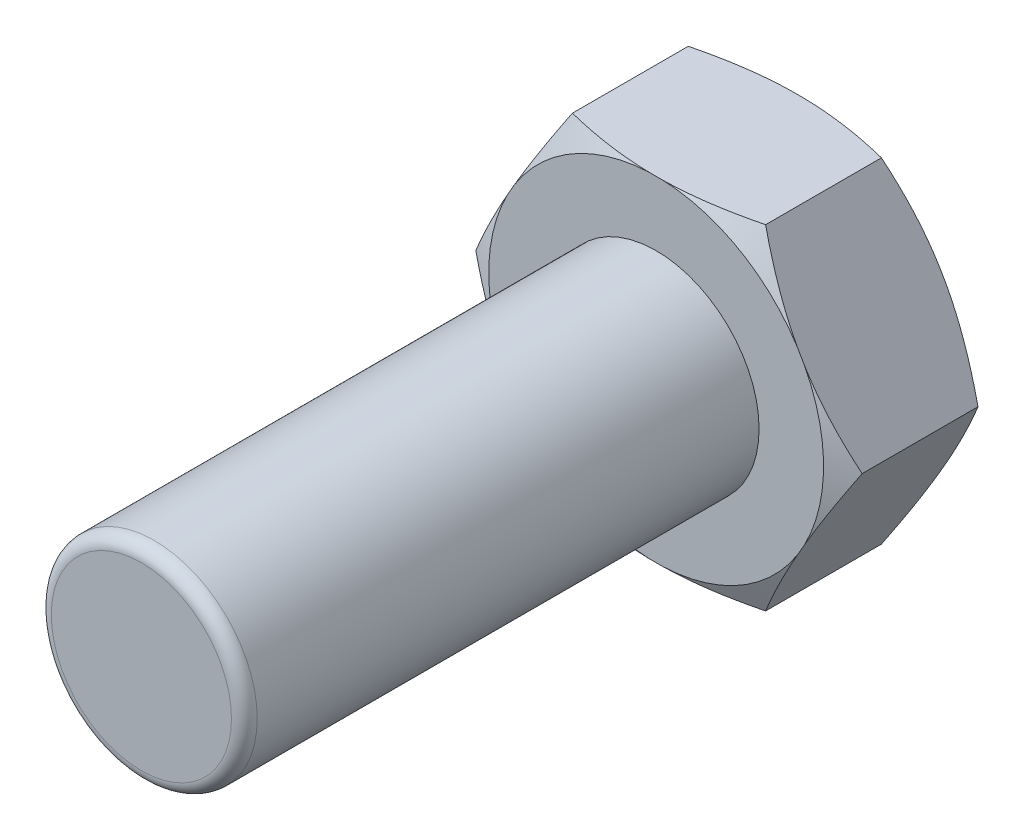
SolidWorks part; units mm, degrees
material "1.0036 (S235JRG1)"
ref_plane "Ön Düzlem" through (0, 0, 0) normal (0, 0, 1) x (1, 0, 0)
ref_plane "Üst Düzlem" through (0, 0, 0) normal (0, 1, 0) x (1, 0, 0)
ref_plane "Sağ Düzlem" through (0, 0, 0) normal (1, 0, 0) x (0, 0, -1)
sketch "Çizim1" plane through (0, 0, 0) normal (0, 0, 1) x (1, 0, 0)
  line L1 (7.5056, 0) -> (3.7528, 6.5)
  line L2 (3.7528, 6.5) -> (-3.7528, 6.5)
  line L3 (-3.7528, 6.5) -> (-7.5056, 0)
  line L4 (-7.5056, 0) -> (-3.7528, -6.5)
  line L5 (-3.7528, -6.5) -> (3.7528, -6.5)
  line L6 (3.7528, -6.5) -> (7.5056, 0)
  circle A0 centre (0, 0) radius 6.5 construction
  dimension "D1" = 13
extrude "Yükseklik-Ekstrüzyon1" add sketch "Çizim1" along normal blind 5.5
sketch "Çizim2" plane through (0, 0, 5.5) normal (0, 0, 1) x (1, 0, 0)
  circle A0 centre (0, 0) radius 4
  dimension "D1" = 8
extrude "Yükseklik-Ekstrüzyon2" add sketch "Çizim2" along normal blind 20
cosmetic thread "Kozmetik Diş Açma1" parameters "D2"=6.619
sketch "Çizim3" plane through (0, 0, 0) normal (0, 1, 0) x (1, 0, 0)
  line L0 (-7.5056, 0) -> (-6.5056, 0)
  line L1 (-3.7528, 0) -> (-7.5056, 0) construction
  line L2 (-6.5056, 0) -> (-7.5056, -0.5)
  line L3 (-7.5056, -5.5) -> (-7.5056, 0) construction
  line L4 (-7.5056, -0.5) -> (-7.5056, 0)
  line L9 (-7.5056, -5.5) -> (-7.5056, -5)
  line L10 (-7.5056, -5) -> (-6.5056, -5.5)
  line L11 (-3.7528, -5.5) -> (-7.5056, -5.5) construction
  line L12 (-6.5056, -5.5) -> (-7.5056, -5.5)
  line L13 (0, 0) -> (0, -5.5) construction
  line L14 (-4, -5.5) -> (4, -5.5) construction
  dimension "D1" = 1
  dimension "D2" = 0.5
  dimension "D3" = 0.5
  dimension "D4" = 1
revolve "Kes-Döndür1" cut sketch "Çizim3" angle 360 about L13
fillet "Radyus1" radius 0.5 1 edges at (4, 0, 25.5)
